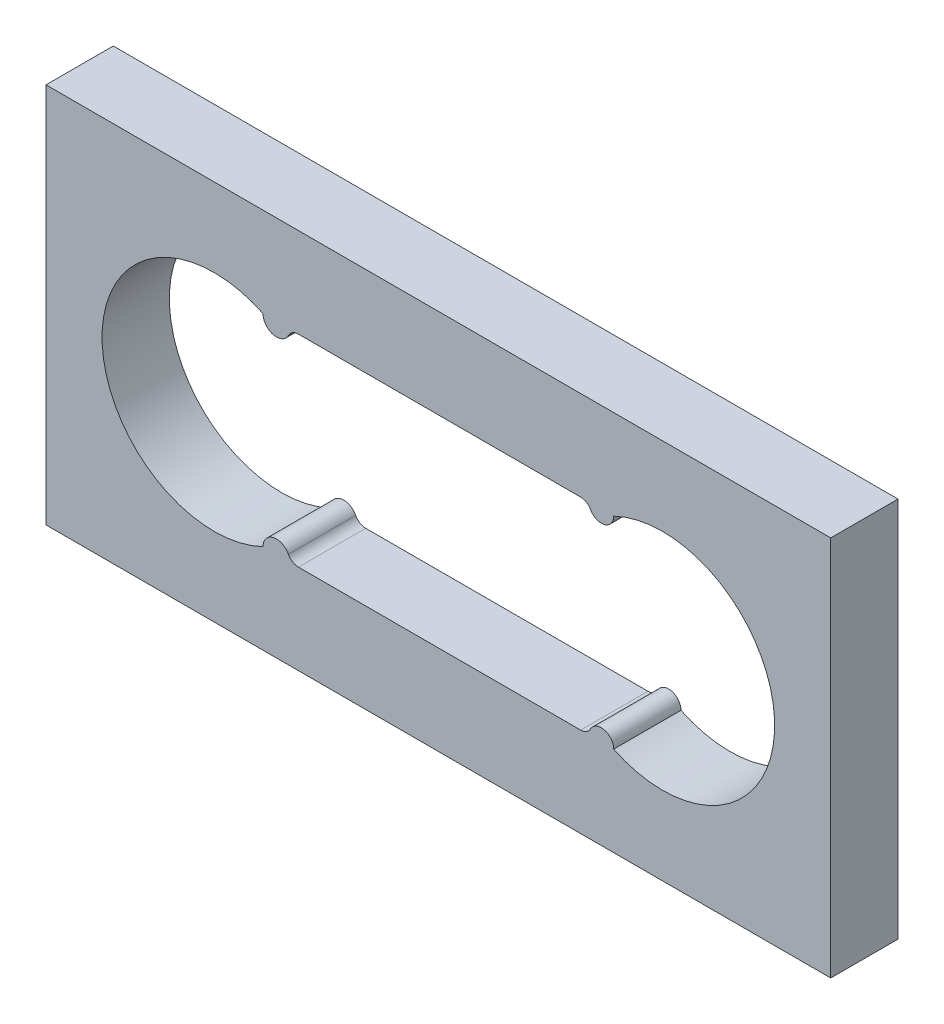
SolidWorks part; units mm, degrees
ref_plane "정면" through (0, 0, 0) normal (0, 0, 1) x (1, 0, 0)
ref_plane "윗면" through (0, 0, 0) normal (0, 1, 0) x (1, 0, 0)
ref_plane "우측면" through (0, 0, 0) normal (1, 0, 0) x (0, 0, -1)
sketch "스케치1" plane through (0, 0, 0) normal (0, 0, 1) x (1, 0, 0)
  line L1 (-17.5, -8.5) -> (17.5, -8.5)
  line L2 (-17.5, -8.5) -> (-17.5, 8.5)
  line L3 (-17.5, 8.5) -> (17.5, 8.5)
  line L4 (17.5, -8.5) -> (17.5, 8.5)
  line L5 (-17.5, -8.5) -> (17.5, 8.5) construction
  line L6 (-17.5, 8.5) -> (17.5, -8.5) construction
  line L7 (-10, -4.5) -> (10, -4.5)
  line L8 (-10, -4.5) -> (-10, 4.5)
  line L9 (-10, 4.5) -> (10, 4.5)
  line L10 (10, -4.5) -> (10, 4.5)
  line L11 (-10, -4.5) -> (10, 4.5) construction
  line L12 (-10, 4.5) -> (10, -4.5) construction
  circle A0 centre (-10, 0) radius 5
  circle A1 centre (10, 0) radius 5
  point P0 (0, 0)
  point P6 (0, 0)
  dimension "D1" = 10
  dimension "D2" = 10
  dimension "D3" = 20
  dimension "D4" = 17
  dimension "D5" = 35
  dimension "D6" = 9
extrude "보스-돌출1" add sketch "스케치1" along normal blind 3 contours L1 L4 L3 L2 A1 L7 A0 L9
sketch "스케치2" plane through (0, 0, 3) normal (0, 0, 1) x (1, 0, 0)
  line L0 (-7.8206, 4.5) -> (7.8206, 4.5) construction
  line L1 (-7.8206, -4.5) -> (7.8206, -4.5) construction
  circle A0 centre (-7.2206, 4.5) radius 0.6
  circle A1 centre (-7.2206, -4.5) radius 0.6
  circle A2 centre (7.2706, -4.5) radius 0.55
  circle A3 centre (7.2706, 4.5) radius 0.55
  dimension "D1" = 1.2
  dimension "D2" = 1.2
  dimension "D3" = 1.1
  dimension "D4" = 1.1
extrude "보스-돌출2" add sketch "스케치2" against normal blind 3
fillet "필렛1" radius 0.5 4 edges at (6.7206, 4.5, 1.5) (6.7206, -4.5, 1.5) (-6.6206, -4.5, 1.5) (-6.6206, 4.5, 1.5)
